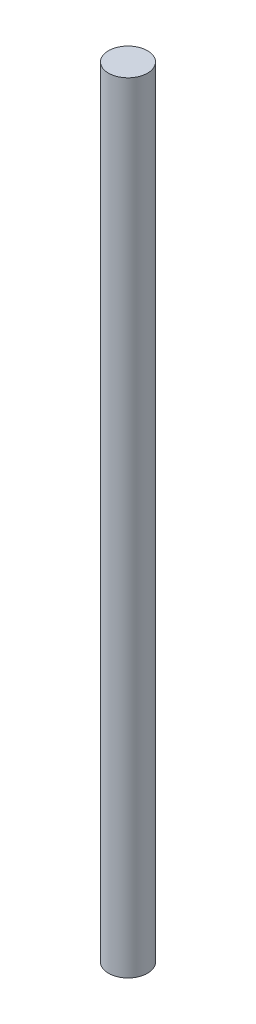
SolidWorks part; units mm, degrees
ref_plane "Front Plane" through (0, 0, 0) normal (0, 0, 1) x (1, 0, 0)
ref_plane "Top Plane" through (0, 0, 0) normal (0, 1, 0) x (1, 0, 0)
ref_plane "Right Plane" through (0, 0, 0) normal (1, 0, 0) x (0, 0, -1)
sketch "Sketch1" plane through (0, 0, 0) normal (0, 1, 0) x (1, 0, 0)
  circle A0 centre (0, 0) radius 1.27
  dimension "D1" = 2.54
extrude "Boss-Extrude1" add sketch "Sketch1" along normal mid plane 50.8
